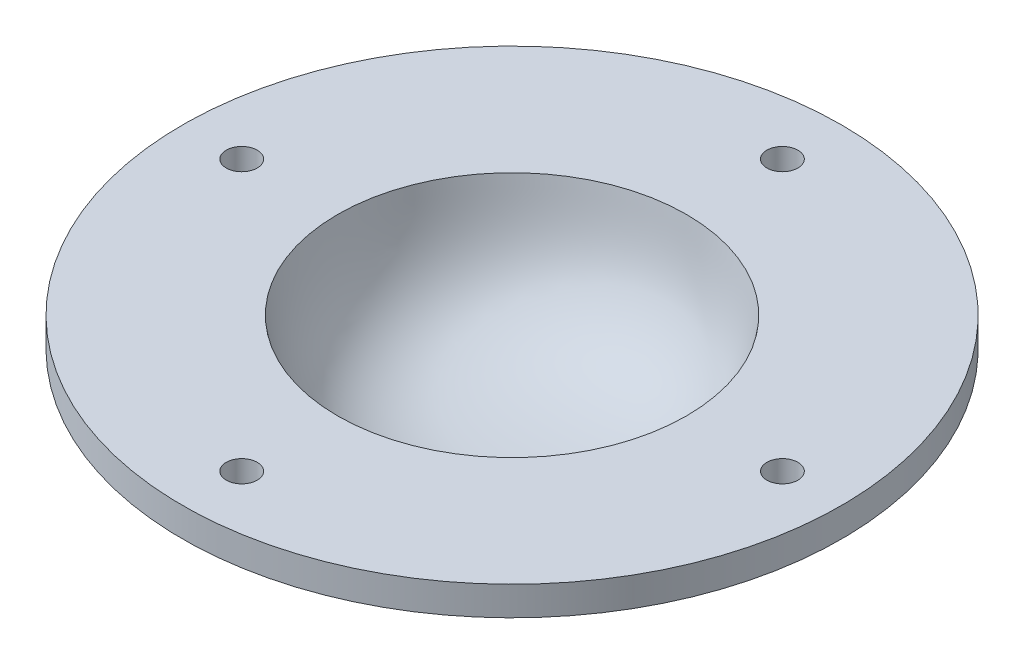
SolidWorks part; units mm, degrees
ref_plane "Front" through (0, 0, 0) normal (0, 0, 1) x (1, 0, 0)
ref_plane "Top" through (0, 0, 0) normal (0, 1, 0) x (1, 0, 0)
ref_plane "Right" through (0, 0, 0) normal (1, 0, 0) x (0, 0, -1)
sketch "Sketch1" plane through (0, 0, 0) normal (0, 0, 1) x (1, 0, 0)
  line L0 (0, -17) -> (0, -14)
  line L1 (-15, 0) -> (15, 0) construction
  line L2 (-15, 0) -> (-15, -9) construction
  line L3 (-15, -9) -> (15, -9) construction
  line L4 (15, 0) -> (15, -9) construction
  line L5 (0, 0) -> (18, 0) construction
  line L6 (18, 0) -> (15.6756, -14.676) construction
  line L7 (-15, -20) -> (15, -20) construction
  line L8 (-15, -17) -> (15, -17) construction
  line L9 (-15, -14) -> (15, -14) construction
  line L10 (18, 0) -> (20.9614, 0)
  line L11 (20.9614, 0) -> (20.9614, -0.4796)
  spline S0 degree 3 poles (0, -14) (16.3895, -14) (17.0195, -6.0548) (18, 0) knots 0 0 0 0 1 1 1 1
  spline S1 degree 1 poles (0, -17) (20.9614, -0.4796) knots 0 0 1 1 construction
  spline S2 degree 3 poles (0, -17) (0.5286, -17) (1.6054, -16.9836) (3.6002, -16.8864) (5.916, -16.6467) (8.4024, -16.1752) (11.3697, -15.3057) (14.4679, -13.7682) (17.227, -11.2724) (19.0168, -8.4145) (20.042, -5.5311) (20.5097, -3.2772) (20.7842, -1.6054) (20.8994, -0.8624) (20.9614, -0.4796) knots 0 0 0 0 0.03125 0.0625 0.125 0.1875 0.25 0.375 0.5 0.625 0.75 0.875 0.9375 1 1 1 1
  dimension "D1" = 30
  dimension "D2" = 9
  dimension "D3" = 18
  dimension "D4" = 20
  dimension "D5" = 3
  dimension "D6" = 3
  dimension "D7" = 81
  dimension "D8" = 3
revolve "Revolve1" add sketch "Sketch1" angle 360 about L0
sketch "Sketch3" plane through (0, 0, 0) normal (0, 0, 1) x (1, 0, 0)
  line L0 (20.5466, 0) -> (34, 0)
  line L1 (20.9614, 0) -> (-20.9614, 0) construction
  line L2 (34, 0) -> (34, -3)
  line L3 (34, -3) -> (20.5466, -3)
  line L4 (20.5466, -3) -> (20.5466, 0)
  line L5 (0, 0) -> (0, 8.9192) construction
  spline S0 degree 3 poles (0, -17) (0.5286, -17) (1.6054, -16.9836) (3.6002, -16.8864) (5.916, -16.6467) (8.4024, -16.1752) (11.3697, -15.3057) (14.4679, -13.7682) (17.227, -11.2724) (19.0168, -8.4145) (20.042, -5.5311) (20.5097, -3.2772) (20.7842, -1.6054) (20.8994, -0.8624) (20.9614, -0.4796) knots 0 0 0 0 0.03125 0.0625 0.125 0.1875 0.25 0.375 0.5 0.625 0.75 0.875 0.9375 1 1 1 1 construction
  dimension "D1" = 3
  dimension "D2" = 34
revolve "Revolve2" add sketch "Sketch3" angle 360 about L5
fillet "Fillet1" radius 1.5 1 edges at (0, -3, -20.5466)
sketch "Sketch4" plane through (0, -3, 0) normal (0, -1, 0) x (1, 0, 0)
  line L0 (0, -34) -> (0, -21.776) construction
  circle A0 centre (0, 0) radius 34 construction
  circle A1 centre (0, 0) radius 21.776 construction
  circle A2 centre (0, -27.888) radius 1.6
  dimension "D1" = 3.2
extrude "Cut-Extrude1" cut sketch "Sketch4" against normal through all
pattern_circular "CirPattern1" count 4 every 90 about axis through (0, 0, 0) along (0, 1, 0) of "Cut-Extrude1"
